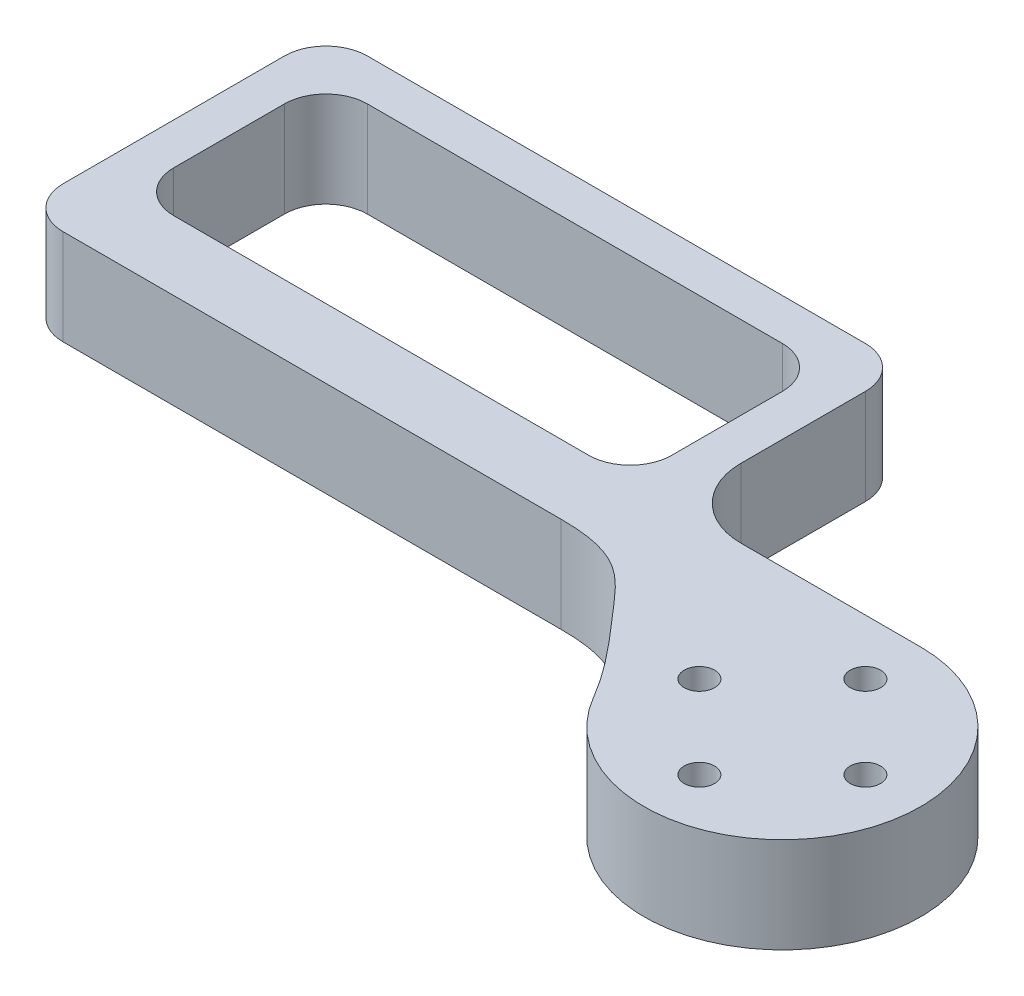
SolidWorks part; units mm, degrees
ref_plane "Front Plane" through (0, 0, 0) normal (0, 0, 1) x (1, 0, 0)
ref_plane "Top Plane" through (0, 0, 0) normal (0, 1, 0) x (1, 0, 0)
ref_plane "Right Plane" through (0, 0, 0) normal (1, 0, 0) x (0, 0, -1)
sketch "Sketch1" plane through (0, 0, 0) normal (0, 1, 0) x (1, 0, 0)
  line L0 (0, 0) -> (0, 6) construction
  line L1 (0, 0) -> (10, 0) construction
  line L2 (0, -6) -> (0, 0) construction
  circle A0 centre (0, 0) radius 10
  circle A1 centre (0, 6) radius 1.1
  circle A2 centre (0, -6) radius 1.1
  circle A3 centre (6, 0) radius 1.1
  circle A4 centre (-6, 0) radius 1.1
  dimension "D1" = 20
  dimension "D2" = 2.2
  dimension "D4" = 2.2
  dimension "D3" = 6
  dimension "D5" = 6
extrude "Boss-Extrude1" add sketch "Sketch1" along normal blind 4
sketch "Sketch2" plane through (0, 4, 0) normal (0, 1, 0) x (1, 0, 0)
  line L0 (-60, 5) -> (-8.6603, 5)
  line L1 (0, 0) -> (-60, 0) construction
  line L2 (-60, 5) -> (-60, 0)
  line L3 (-60, 0) -> (-60, -5)
  line L4 (-60, -5) -> (-8.6603, -5)
  circle A0 centre (0, 0) radius 10 construction
  circle A1 centre (0, 0) radius 10
  circle M7 centre (0, 0) radius 10
  dimension "D1" = 10
  dimension "D2" = 60
extrude "Boss-Extrude2" add sketch "Sketch2" against normal up to surface (4 mm away) contours L1 L0 L2 M7 | A1 L1 L3 L4 up to face at (0, 0, 10)
sketch "Sketch7" plane through (0, 4, 0) normal (0, 1, 0) x (1, 0, 0)
  line L0 (-60, 5) -> (-60, 10)
  line L1 (-60, 10) -> (0, 10)
  line L2 (-60, 5) -> (-8.6603, 5) construction
  line L3 (-60, 5) -> (-8.6603, 5)
  arc A0 (-8.6603, -5) -> (-8.6603, 5) centre (0, 0) ccw construction
  arc A1 (-8.6603, -5) -> (-8.6603, 5) centre (0, 0) ccw
  circle M2 centre (6, 0) radius 1.1
  circle M3 centre (0, 6) radius 1.1
  arc M4 (-8.6603, -5) -> (-8.6603, 5) centre (0, 0) ccw
  line M5 (-8.6603, 5) -> (-60, 5)
  line M6 (-60, 5) -> (-60, -5)
  line M7 (-60, -5) -> (-8.6603, -5)
  circle M8 centre (0, -6) radius 1.1
  circle M9 centre (-6, 0) radius 1.1
extrude "Boss-Extrude5" add sketch "Sketch7" against normal up to surface (4 mm away) contours L1 L0 M5 M4 | M7 M4 M5 M6 M3 M8 M9 M2 up to face at (-29.6651, 0, 0)
sketch "Sketch5" plane through (0, 4, 0) normal (0, 1, 0) x (1, 0, 0)
  line L1 (-60, 10) -> (-18, 10)
  line L2 (-60, 10) -> (-60, 27)
  line L3 (-60, 27) -> (-18, 27)
  line L4 (-18, 10) -> (-18, 27)
  line L5 (-57, 10) -> (-21, 10)
  line L6 (-57, 10) -> (-57, 24)
  line L7 (-57, 24) -> (-21, 24)
  line L8 (-21, 10) -> (-21, 24)
  line L9 (-60, 10) -> (-18, 10)
  line L10 (-60, 10) -> (-60, 7)
  line L11 (-60, 7) -> (-18, 7)
  line L12 (-18, 10) -> (-18, 7)
  point P9 (-39, 24)
  point P10 (-39, 27)
  dimension "D1" = 42
  dimension "D2" = 3
  dimension "D3" = 3
  dimension "D4" = 14
  dimension "D5" = 3
extrude "Boss-Extrude3" add sketch "Sketch5" against normal blind 6.9
fillet "Fillet1" radius 3 2 edges at (-60, 0.55, -27) (-18, 0.55, -27)
fillet "Fillet2" radius 3 4 edges at (-21, 0.55, -10) (-57, 0.55, -10) (-57, 0.55, -24) (-21, 0.55, -24)
fillet "Fillet3" radius 5 1 edges at (-18, 2, -10)
sketch "Sketch9" plane through (0, 4, 0) normal (0, 1, 0) x (1, 0, 0)
  line L0 (-21, 5) -> (-60, 5)
  line L1 (-60, 24) -> (-60, -5) construction
  line L2 (-54, 10) -> (-24, 10) construction
  line L3 (-60, 5) -> (-60, -5)
  line L4 (-60, -5) -> (-8.6603, -5)
  line L5 (-60, -5) -> (-8.6603, -5) construction
  line L6 (-21, 13) -> (-21, 5) construction
  arc A0 (-8.6603, -5) -> (0, 10) centre (0, 0) ccw construction
  spline S0 degree 3 poles (-8.6603, -5) (-10.002, -2.676) (-14.6498, 2.4691) (-16.537, 5) (-21, 5) knots 0 0 0 0 0.396923 1 1 1 1
  dimension "D1" = 5
  dimension "D2" = 46.7433
  dimension "D3" = 5.9966
extrude "Cut-Extrude4" cut sketch "Sketch9" against normal through all
sketch "Sketch10" plane through (0, 0, 0) normal (0, -1, 0) x (1, 0, 0)
  line L0 (-18, -7) -> (-18, -4.6704)
  line L6 (-21, -5) -> (-60, -5)
  line L7 (-60, -5) -> (-60, -7)
  line L8 (-60, -7) -> (-18, -7)
  line L9 (-18, -7) -> (-18, -15)
  line L10 (-13, -10) -> (0, -10)
  line L11 (-21, -5) -> (-60, -5)
  line L12 (-60, -5) -> (-60, -7)
  line L13 (-60, -7) -> (-18, -7)
  arc A2 (0, -10) -> (-8.6603, 5) centre (0, 0) ccw
  arc A3 (-13, -10) -> (-18, -15) centre (-13, -15) ccw
  spline S0 degree 3 poles (-8.6603, 5) (-10.002, 2.676) (-14.6498, -2.4691) (-16.537, -5) (-21, -5) knots 0 0 0 0 0.396923 1 1 1 1 construction
  spline S2 degree 3 poles (-3003.5903, -102.9314) (131.726, 145.3335) (-101.7283, -84.288) (29.2427, 31.1932) (-2963.2769, 579.101) knots -5.676647 -5.676647 -5.676647 -5.676647 0.396923 5.812782 5.812782 5.812782 5.812782 only from (-8.6603, 5) to (-21, -5)
  spline S3 degree 3 poles (-18, -4.6704) (-18.8109, -4.8862) (-19.7815, -5) (-21, -5) knots 0.835352 0.835352 0.835352 0.835352 1 1 1 1
  spline M10 degree 3 poles (-8.6603, 5) (-10.002, 2.676) (-14.6498, -2.4691) (-16.537, -5) (-21, -5) knots 0 0 0 0 0.396923 1 1 1 1
  line M11 (-21, -5) -> (-60, -5)
  line M12 (-60, -5) -> (-60, -7)
  line M13 (-60, -7) -> (-18, -7)
  dimension "D1" = 0
extrude "Boss-Extrude7" add sketch "Sketch10" along normal up to surface (2.9 mm away) contours L0 M13 M10 M11 M12
fillet "Fillet5" radius 3 1 edges at (-60, 0.55, -5)
sketch "Sketch11" plane through (0, 0, 0) normal (0, -1, 0) x (1, 0, 0)
  line L2 (-18, -4.6704) -> (-18, -15)
  line L3 (-13, -10) -> (0, -10)
  line L4 (-18, -4.6704) -> (-18, -15)
  line L5 (-13, -10) -> (0, -10)
  circle A0 centre (0, 0) radius 8.15
  arc A3 (-13, -10) -> (-18, -15) centre (-13, -15) ccw
  arc A4 (0, -10) -> (-8.6603, 5) centre (0, 0) ccw
  arc A5 (-13, -10) -> (-18, -15) centre (-13, -15) ccw
  arc A6 (0, -10) -> (-8.6603, 5) centre (0, 0) ccw
  spline S1 degree 3 poles (-3003.5981, -102.932) (131.7262, 145.3337) (-101.6928, -84.2531) (29.2029, 31.1581) (-2960.3813, 578.5708) knots -5.676652 -5.676652 -5.676652 -5.676652 0.396923 5.811035 5.811035 5.811035 5.811035 only from (-8.6603, 5) to (-18, -4.6704)
  spline S2 degree 3 poles (-8.6603, 5) (-10.002, 2.676) (-13.8846, -1.622) (-15.8407, -4.0957) (-18, -4.6704) knots 0 0 0 0 0.396923 0.835352 0.835352 0.835352 0.835352
  spline M11 degree 3 poles (-8.6603, 5) (-10.002, 2.676) (-14.6498, -2.4691) (-16.537, -5) (-21, -5) knots 0 0 0 0 0.396923 1 1 1 1 only from (-8.6603, 5) to (-18, -4.6704)
  line M12 (-18, -4.6704) -> (-18, -15)
  arc M13 (-18, -15) -> (-13, -10) centre (-13, -15) cw
  line M14 (-13, -10) -> (0, -10)
  arc M15 (0, -10) -> (-8.6603, 5) centre (0, 0) ccw
  dimension "D1" = 16.3
  dimension "D2" = 0
extrude "Boss-Extrude8" add sketch "Sketch11" along normal blind 2.9 contours A0 M15 M11 M12 M13 M14 | S2 L4 A5 L5 A6
